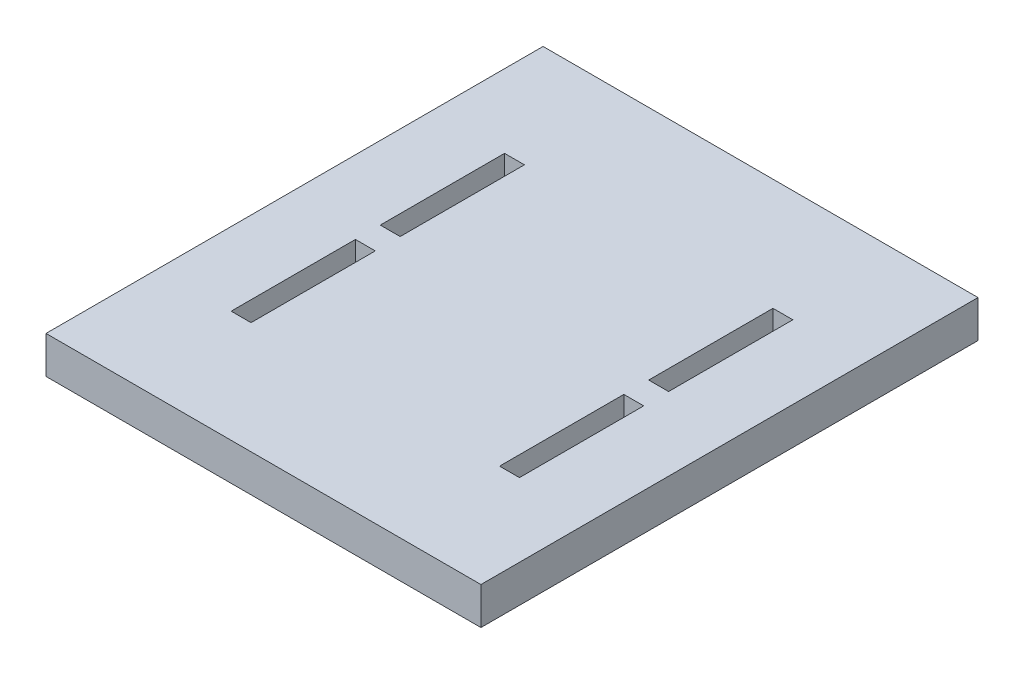
SolidWorks part; units mm, degrees
ref_plane "前视基准面" through (0, 0, 0) normal (0, 0, 1) x (1, 0, 0)
ref_plane "上视基准面" through (0, 0, 0) normal (0, 1, 0) x (1, 0, 0)
ref_plane "右视基准面" through (0, 0, 0) normal (1, 0, 0) x (0, 0, -1)
other "Configuration Table"
sketch "草图1" plane through (0, 0, 0) normal (0, 1, 0) x (1, 0, 0)
  line L0 (35, 0) -> (35, -80)
  line L1 (0, 0) -> (70, 0)
  line L2 (0, 0) -> (0, -80)
  line L3 (0, -80) -> (70, -80)
  line L4 (70, 0) -> (70, -80)
  line L9 (0, -40) -> (70, -40)
  line L23 (11.8, -18) -> (15, -18)
  line L24 (11.8, -18) -> (11.8, -38)
  line L25 (11.8, -38) -> (15, -38)
  line L26 (15, -18) -> (15, -38)
  line L32 (11.8, -42) -> (15, -42)
  line L33 (15, -62) -> (15, -42)
  line L34 (11.8, -62) -> (15, -62)
  line L35 (11.8, -62) -> (11.8, -42)
  line L44 (58.2, -62) -> (58.2, -42)
  line L45 (58.2, -62) -> (55, -62)
  line L46 (55, -62) -> (55, -42)
  line L47 (58.2, -42) -> (55, -42)
  line L48 (58.2, -38) -> (55, -38)
  line L49 (55, -18) -> (55, -38)
  line L50 (58.2, -18) -> (55, -18)
  line L51 (58.2, -18) -> (58.2, -38)
  dimension "D1" = 70
  dimension "D2" = 80
  dimension "D3" = 2
  dimension "D7" = 3.2
  dimension "D8" = 20
  dimension "D9" = 20
extrude "凸台-拉伸1" add sketch "草图1" along normal blind 6
